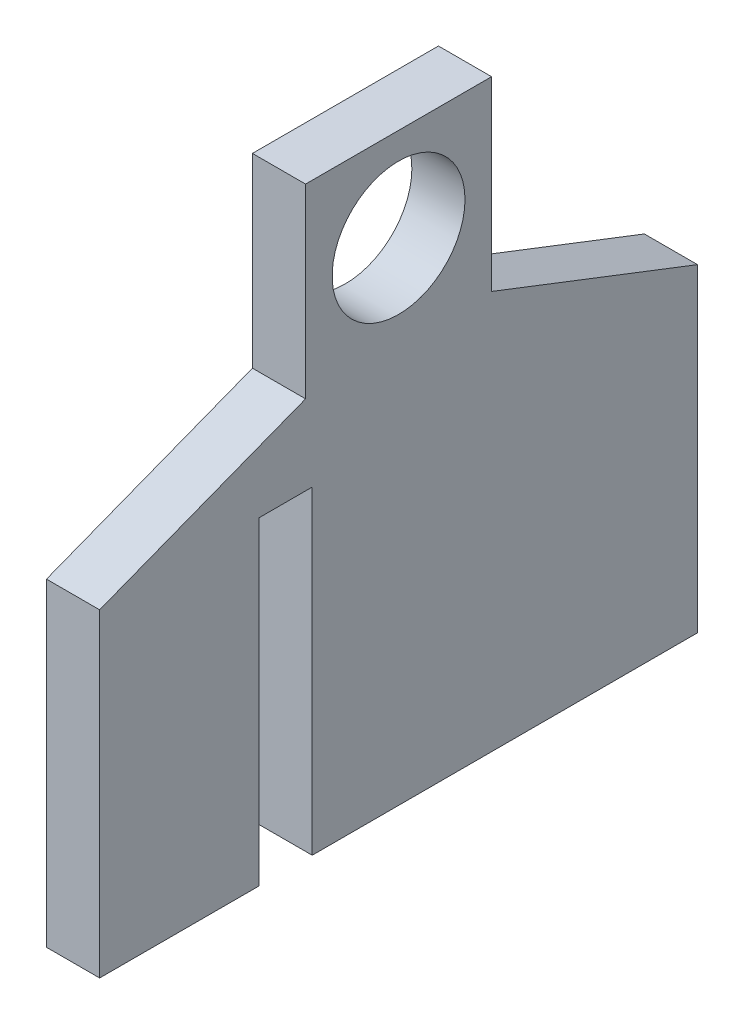
SolidWorks part; units mm, degrees
material "Perspex (TM) GS Acrylic Cast Sheet"
ref_plane "Front Plane" through (0, 0, 0) normal (0, 0, 1) x (1, 0, 0)
ref_plane "Top Plane" through (0, 0, 0) normal (0, 1, 0) x (1, 0, 0)
ref_plane "Right Plane" through (0, 0, 0) normal (1, 0, 0) x (0, 0, -1)
sketch "Sketch1" plane through (0, 0, 0) normal (1, 0, 0) x (0, 0, -1)
  line L0 (-11.25, 0) -> (-5.25, 0)
  line L1 (11.25, 0) -> (11.25, 12)
  line L2 (11.25, 12) -> (3.5, 15)
  line L3 (3.5, 15) -> (3.5, 22)
  line L4 (3.5, 22) -> (-3.5, 22)
  line L5 (-3.5, 22) -> (-3.5, 15)
  line L6 (-3.5, 15) -> (-11.25, 12)
  line L7 (-11.25, 12) -> (-11.25, 0)
  line L8 (-5.25, 0) -> (-5.25, 12)
  line L9 (-5.25, 12) -> (-3.25, 12)
  line L10 (-3.25, 12) -> (-3.25, 0)
  line L11 (-3.25, 0) -> (11.25, 0)
  circle A0 centre (0, 18.5) radius 2.5
  point P15 (0, 22)
  point P16 (-3.5, 18.5)
  point P17 (0, 0)
  point P18 (0, 0)
  dimension "D9" = 5
  dimension "D1" = 12
  dimension "D2" = 3
  dimension "D3" = 7
  dimension "D4" = 7
  dimension "D5" = 22.5
  dimension "D6" = 2
  dimension "D7" = 6
extrude "Boss-Extrude1" add sketch "Sketch1" along normal blind 2
